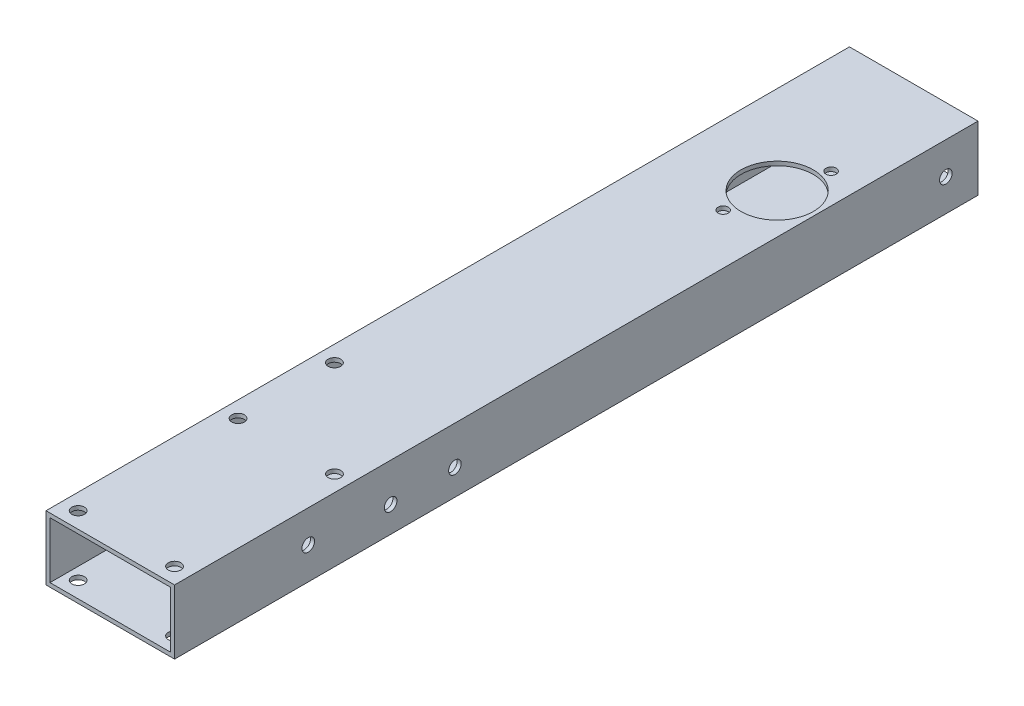
SolidWorks part; units mm, degrees
material "6061 Alloy"
ref_plane "Front Plane" through (0, 0, 0) normal (0, 0, 1) x (1, 0, 0)
ref_plane "Top Plane" through (0, 0, 0) normal (0, 1, 0) x (1, 0, 0)
ref_plane "Right Plane" through (0, 0, 0) normal (1, 0, 0) x (0, 0, -1)
sketch "Sketch1" plane through (0, 0, 0) normal (0, 0, 1) x (1, 0, 0)
  line L0 (-23.8125, 11.1125) -> (23.8125, 11.1125)
  line L2 (-25.4, 12.7) -> (25.4, 12.7)
  line L3 (-25.4, 12.7) -> (-25.4, -12.7)
  line L4 (-25.4, -12.7) -> (25.4, -12.7)
  line L5 (25.4, 12.7) -> (25.4, -12.7)
  line L10 (23.8125, 11.1125) -> (23.8125, -11.1125)
  line L11 (-23.8125, -11.1125) -> (23.8125, -11.1125)
  line L12 (-23.8125, 11.1125) -> (-23.8125, -11.1125)
  point P12 (0, 12.7)
  point P14 (25.4, 0)
  dimension "Wall Thickness" = 1.5875
  dimension "Outside Width" = 50.8
  dimension "Outside Height" = 25.4
  dimension "Inside Height" = 22.225
  dimension "Inside Width" = 47.625
sketch "Sketch2" plane through (0, 0, 0) normal (1, 0, 0) x (0, 0, -1)
  line L0 (158.75, 0) -> (-158.75, 0)
  point P4 (0, 0)
  point P7 (-158.75, 0)
  point P10 (158.75, 0)
  dimension "Length" = 317.5
sketch "Sketch3" plane through (0, 0, 0) normal (0, 0, 1) x (1, 0, 0)
  line L21 (25.4, 12.7) -> (-25.4, 12.7)
  line L22 (25.4, -12.7) -> (25.4, 12.7)
  line L23 (-25.4, -12.7) -> (25.4, -12.7)
  line L24 (-25.4, 12.7) -> (-25.4, -12.7)
  line L25 (25.4, 12.7) -> (-25.4, 12.7)
  line L26 (25.4, -12.7) -> (25.4, 12.7)
  line L27 (-25.4, -12.7) -> (25.4, -12.7)
  line L28 (-25.4, 12.7) -> (-25.4, -12.7)
  line L29 (23.8125, 11.1125) -> (-23.8125, 11.1125)
  line L30 (23.8125, -11.1125) -> (23.8125, 11.1125)
  line L31 (-23.8125, -11.1125) -> (23.8125, -11.1125)
  line L32 (-23.8125, 11.1125) -> (-23.8125, -11.1125)
  line L33 (23.8125, 11.1125) -> (-23.8125, 11.1125)
  line L34 (23.8125, -11.1125) -> (23.8125, 11.1125)
  line L35 (-23.8125, -11.1125) -> (23.8125, -11.1125)
  line L36 (-23.8125, 11.1125) -> (-23.8125, -11.1125)
  dimension "D1" = 0
  dimension "D2" = 0
extrude "Boss-Extrude1" add sketch "Sketch3" along normal up to vertex (158.75 mm away) and the other way up to vertex (158.75 mm away) up to point (0, 0, 158.75) other way up to point (0, 0, -158.75)
sketch "Drawing Reference" plane through (0, 0, 0) normal (1, 0, 0) x (0, 0, -1)
  line L0 (-158.75, 0) -> (158.75, 0) construction
  line L1 (0, -12.7) -> (0, 12.7) construction
  line L2 (-158.75, -12.7) -> (158.75, -12.7) construction
  line L5 (-158.75, 12.7) -> (158.75, 12.7) construction
  point P7 (-122.174, 0)
  point P8 (122.174, 0)
  dimension "D1" = 36.576
sketch "Sketch4" plane through (0, 12.7, 0) normal (0, 1, 0) x (1, 0, 0)
  line L0 (0, 158.75) -> (0, 95.25) construction
  line L1 (25.4, 158.75) -> (-25.4, 158.75) construction
  line L2 (0, 95.25) -> (9.525, 95.25) construction
  line L3 (0, 158.75) -> (0, -26.67) construction
  circle A1 centre (9.525, 95.25) radius 14.2875
  circle A3 centre (9.525, 95.25) radius 117.5004 construction
  dimension "D1" = 63.5
  dimension "D3" = 235.0008
  dimension "D2" = 9.525
extrude "Cut-Extrude1" cut sketch "Sketch4" against normal blind 39.37
sketch "Sketch5" plane through (-25.4, 0, 0) normal (-1, 0, 0) x (0, 0, 1)
  line L0 (73.3582, -2.425) -> (47.9582, -2.425) construction
hole_wizard "#10 Clearance Hole1" positions "Sketch6" profile "Sketch7" hole size "#10" standard "ANSI Inch" end condition through all
sketch "Sketch6" plane through (-25.4, 0, 0) normal (-1, 0, 0) x (0, 0, 1)
  point P0 (73.3582, -2.425)
  point P3 (47.9582, -2.425)
sketch "Sketch7" plane through (-25.4, -2.425, 73.3582) normal (0, 1, 0) x (0, 0, 1)
  line L0 (0, 0) -> (0, 50.8)
  line L1 (0, 50.8) -> (2.4892, 50.8)
  line L2 (2.4892, 50.8) -> (2.4892, 0)
  line L5 (2.4892, 0) -> (0, 0)
  line L11 (0, -6.35) -> (0, 107.95) construction
  dimension "Thru Hole Dia." = 4.9784
  dimension "Thru Hole Depth" = 50.8
hole_wizard "#10 Clearance Hole2" positions "Sketch8" profile "Sketch9" hole size "#10" standard "ANSI Inch" end condition through all
sketch "Sketch8" plane through (0, -12.7, 0) normal (0, -1, 0) x (-1, 0, 0)
  point P0 (19.05, -51.1131)
  point P3 (19.05, -89.2131)
  point P6 (-19.05, -89.2131)
  point P9 (-19.05, -152.4)
  point P12 (19.05, -152.4)
sketch "Sketch9" plane through (-19.05, -12.7, 51.1131) normal (1, 0, 0) x (0, 0, -1)
  line L0 (0, 0) -> (0, 25.4)
  line L1 (0, 25.4) -> (2.4892, 25.4)
  line L2 (2.4892, 25.4) -> (2.4892, 0)
  line L5 (2.4892, 0) -> (0, 0)
  line L11 (0, -6.35) -> (0, 107.95) construction
  dimension "Thru Hole Dia." = 4.9784
  dimension "Thru Hole Depth" = 25.4
hole_wizard "#20 (0.161) Diameter Hole1" positions "Sketch10" profile "Sketch11" hole size "#20" standard "ANSI Inch" end condition through all
sketch "Sketch10" plane through (0, 12.7, 0) normal (0, 1, 0) x (1, 0, 0)
  point P0 (13.5246, 112.5743)
  point P3 (5.5254, 77.9257)
sketch "Sketch11" plane through (13.5246, 12.7, -112.5743) normal (1, 0, 0) x (0, 0, 1)
  line L0 (0, 0) -> (0, 25.4)
  line L1 (0, 25.4) -> (2.0447, 25.4)
  line L2 (2.0447, 25.4) -> (2.0447, 0)
  line L5 (2.0447, 0) -> (0, 0)
  line L11 (0, -6.35) -> (0, 107.95) construction
  dimension "Thru Hole Dia." = 4.0894
  dimension "Thru Hole Depth" = 25.4
hole_wizard "#10 Clearance Hole3" positions "Sketch12" profile "Sketch13" hole size "#10" standard "ANSI Inch"
sketch "Sketch12" plane through (25.4, 0, 0) normal (1, 0, 0) x (0, 0, -1)
  point P0 (-105.918, 0)
  point P3 (146.05, 0)
sketch "Sketch13" plane through (25.4, 0, 105.918) normal (0, 1, 0) x (0, 0, -1)
  line L0 (0, 0) -> (0, 14.1957)
  line L1 (0, 14.1957) -> (2.4892, 12.7)
  line L2 (2.4892, 12.7) -> (2.4892, 0)
  line L5 (2.4892, 0) -> (0, 0)
  line L10 (0, 14.1957) -> (-2.4892, 12.7) construction
  line L11 (0, -6.35) -> (0, 107.95) construction
  dimension "Hole Dia." = 4.9784
  dimension "Hole Depth" = 12.7
  dimension "Drill Angle" = 118
equation "\"D1@Drawing Reference\"=\"Outside Width@Sketch1\" * 0.72"
